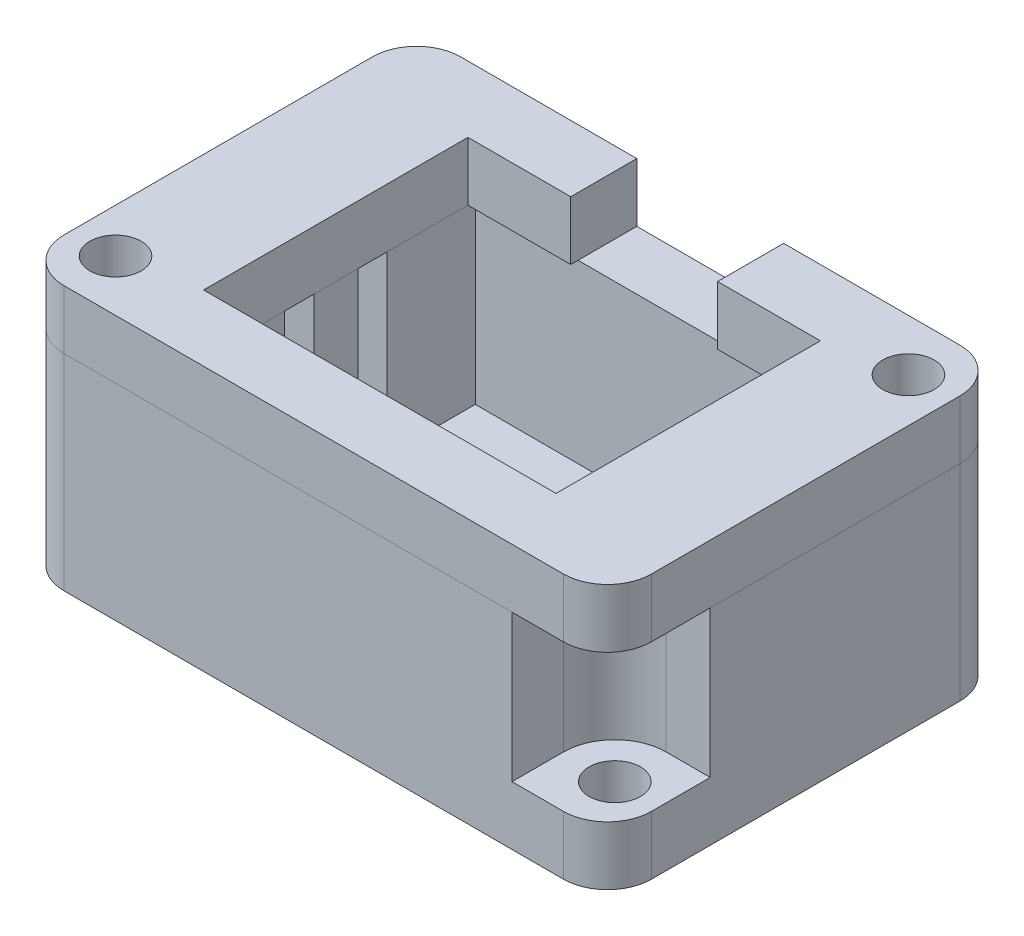
SolidWorks part; units mm, degrees
material "3D printed plastic"
ref_plane "Front Plane" through (0, 0, 0) normal (0, 0, 1) x (1, 0, 0)
ref_plane "Top Plane" through (0, 0, 0) normal (0, 1, 0) x (1, 0, 0)
ref_plane "Right Plane" through (0, 0, 0) normal (1, 0, 0) x (0, 0, -1)
sketch "Sketch1" plane through (0, 0, 0) normal (0, 1, 0) x (1, 0, 0)
  line L0 (12, -3.5) -> (12, -9.5)
  line L1 (-12, 9.5) -> (12, 9.5)
  line L2 (-12, 9.5) -> (-12, 3.5)
  line L3 (-12, -9.5) -> (12, -9.5)
  line L4 (12, 9.5) -> (12, 3.5)
  line L5 (-12, 1.5) -> (-16, 1.5)
  line L6 (-12, -3.5) -> (-12, -9.5)
  line L7 (-12, 3.5) -> (-16, 3.5)
  line L8 (-16, 1.5) -> (-16, 3.5)
  line L9 (-12, -1.5) -> (-16, -1.5)
  line L10 (-12, 9.5) -> (12, -9.5) construction
  line L11 (-12, -3.5) -> (-16, -3.5)
  line L12 (-16, -1.5) -> (-16, -3.5)
  line L13 (12, 1.5) -> (16, 1.5)
  line L14 (-12, 1.5) -> (-12, -1.5)
  line L15 (12, 3.5) -> (16, 3.5)
  line L16 (16, 1.5) -> (16, 3.5)
  line L17 (12, -1.5) -> (16, -1.5)
  line L18 (12, 1.5) -> (12, -1.5)
  line L19 (12, -3.5) -> (16, -3.5)
  line L20 (16, -1.5) -> (16, -3.5)
  line L21 (20, 13.5) -> (-20, -13.5) construction
  line L22 (-20, 13.5) -> (20, 13.5)
  line L23 (-20, 13.5) -> (-20, -13.5)
  line L24 (-20, -13.5) -> (20, -13.5)
  line L25 (20, 13.5) -> (20, -13.5)
  dimension "D1" = 2
  dimension "D2" = 4
  dimension "D3" = 3
  dimension "D4" = 32
  dimension "D5" = 6
  dimension "D6" = 4
  dimension "D7" = 4
extrude "Boss-Extrude1" add sketch "Sketch1" along normal blind 12
sketch "Sketch2" plane through (0, 0, 0) normal (0, -1, 0) x (1, 0, 0)
  line L1 (-20, 13.5) -> (20, 13.5)
  line L2 (-20, 13.5) -> (-20, -13.5)
  line L3 (-20, -13.5) -> (20, -13.5)
  line L4 (20, 13.5) -> (20, -13.5)
extrude "Boss-Extrude2" add sketch "Sketch2" along normal blind 2
sketch "Sketch3" plane through (0, 12, 0) normal (0, 1, 0) x (1, 0, 0)
  line L0 (-17, 10) -> (-17, -10) construction
  line L1 (-17, -10) -> (17, -10) construction
  line L2 (17, -10) -> (17, 10) construction
  line L3 (17, 10) -> (-17, 10) construction
  line L4 (-17, 10) -> (17, -10) construction
  circle A0 centre (-17, 10) radius 1.25
  circle A1 centre (17, 10) radius 1.25
  circle A2 centre (17, -10) radius 1.25
  circle A3 centre (-17, -10) radius 1.25
  dimension "D1" = 2.5
  dimension "D2" = 20
  dimension "D3" = 34
extrude "Cut-Extrude1" cut sketch "Sketch3" against normal through all
fillet "Fillet1" radius 3 4 edges at (-20, 5, -13.5) (20, 5, -13.5) (20, 5, 13.5) (-20, 5, 13.5)
sketch "Sketch4" plane through (0, 12, 0) normal (0, 1, 0) x (1, 0, 0)
  circle A0 centre (-17, 10) radius 1.75
  circle A1 centre (17, -10) radius 1.75
  dimension "D1" = 3.5
extrude "Cut-Extrude2" cut sketch "Sketch4" against normal through all
sketch "Sketch5" plane through (0, 12, 0) normal (0, 1, 0) x (1, 0, 0)
  line L0 (-17, 6.5) -> (-20, 6.5)
  line L1 (-20, 10.5) -> (-20, -10.5) construction
  line L2 (-20, 6.5) -> (-20, 13.5)
  line L3 (-20, 13.5) -> (-13.5, 13.5)
  line L4 (17, 13.5) -> (-17, 13.5) construction
  line L5 (-13.5, 13.5) -> (-13.5, 10)
  line L6 (17, -6.5) -> (20, -6.5)
  line L7 (20, -10.5) -> (20, 10.5) construction
  line L8 (20, -6.5) -> (20, -13.5)
  line L9 (20, -13.5) -> (13.5, -13.5)
  line L10 (-17, -13.5) -> (17, -13.5) construction
  line L11 (13.5, -13.5) -> (13.5, -10)
  arc A0 (-17, 6.5) -> (-13.5, 10) centre (-17, 10) ccw
  arc A1 (17, -6.5) -> (13.5, -10) centre (17, -10) ccw
  dimension "D1" = 7
extrude "Cut-Extrude3" cut sketch "Sketch5" against normal offset from surface (10 mm away) 4 up to face at (17, -2, 11.75)
sketch "Sketch6" plane through (0, 12, 0) normal (0, 1, 0) x (1, 0, 0)
  line L1 (12, 3.5) -> (12, 9.5) construction
  line L3 (-5, 13.5) -> (-5, 9)
  line L4 (-20, 10.5) -> (-20, -10.5)
  line L5 (17, 13.5) -> (-17, 13.5)
  line L6 (20, -10.5) -> (20, 10.5)
  line L7 (-17, -13.5) -> (17, -13.5)
  line L8 (-20, 10.5) -> (-20, -10.5)
  line L9 (17, 13.5) -> (5, 13.5)
  line L10 (20, -10.5) -> (20, 10.5)
  line L11 (-17, -13.5) -> (17, -13.5)
  line L13 (5, 13.5) -> (5, 9)
  line L14 (12, 9) -> (5, 9)
  line L15 (12, 9) -> (12, -9)
  line L16 (12, -9) -> (-12, -9)
  line L17 (-12, 9) -> (-12, -9)
  line L18 (-12, -3.5) -> (-12, -9.5) construction
  line L19 (-5, 9) -> (-12, 9)
  line L20 (-5, 13.5) -> (-17, 13.5)
  line L21 (12, 9.5) -> (-12, 9.5) construction
  line L22 (-12, 9) -> (12, -9) construction
  circle A0 centre (-17, -10) radius 1.75
  circle A1 centre (17, 10) radius 1.75
  arc A4 (-17, 13.5) -> (-20, 10.5) centre (-17, 10.5) ccw
  arc A5 (20, 10.5) -> (17, 13.5) centre (17, 10.5) ccw
  arc A6 (17, -13.5) -> (20, -10.5) centre (17, -10.5) ccw
  arc A7 (-20, -10.5) -> (-17, -13.5) centre (-17, -10.5) ccw
  arc A8 (-17, 13.5) -> (-20, 10.5) centre (-17, 10.5) ccw
  arc A9 (20, 10.5) -> (17, 13.5) centre (17, 10.5) ccw
  arc A10 (17, -13.5) -> (20, -10.5) centre (17, -10.5) ccw
  arc A11 (-20, -10.5) -> (-17, -13.5) centre (-17, -10.5) ccw
  dimension "D2" = 3.5
  dimension "D3" = 10
  dimension "D4" = 0.5
  dimension "D1" = 0
extrude "Boss-Extrude3" add sketch "Sketch6" along normal blind 4 separate body
